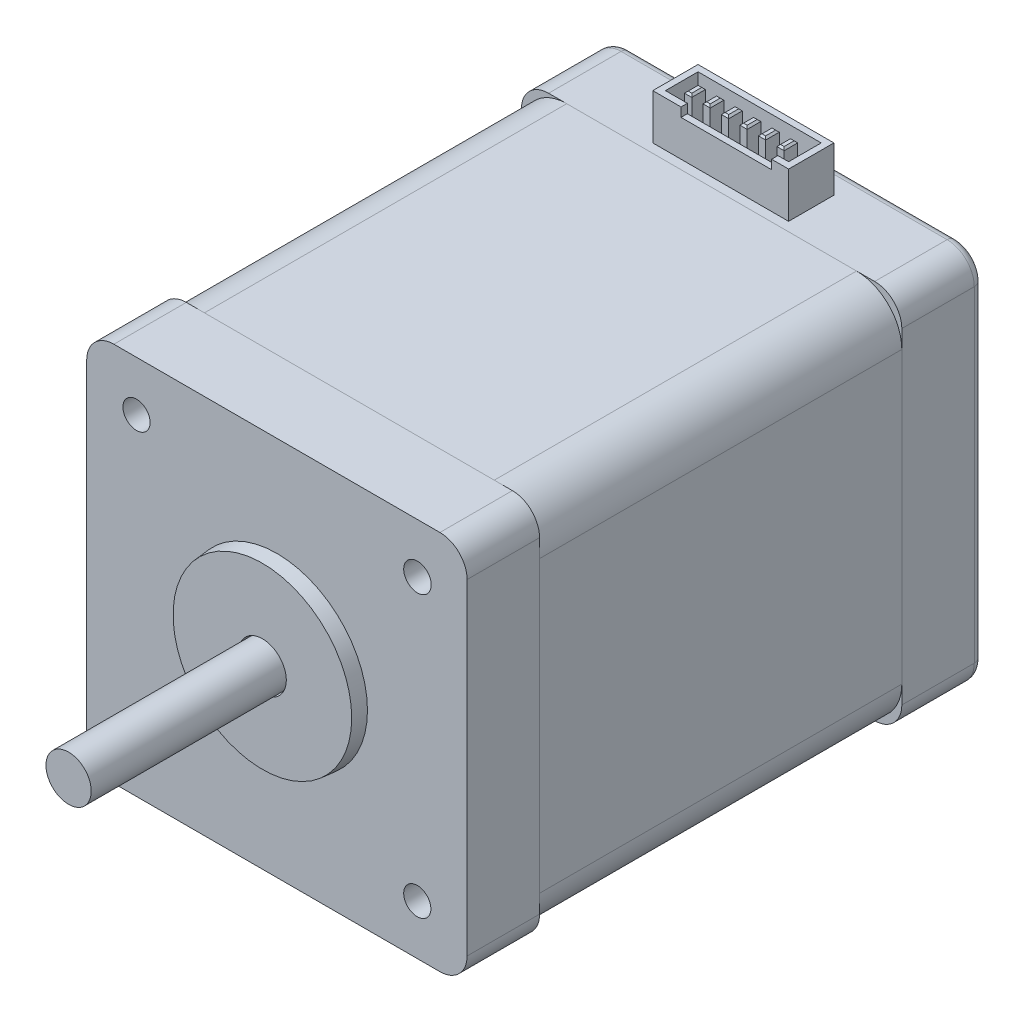
SolidWorks part; units mm, degrees
material "氧化铝"
ref_plane "前视基准面" through (0, 0, 0) normal (0, 0, 1) x (1, 0, 0)
ref_plane "上视基准面" through (0, 0, 0) normal (0, 1, 0) x (1, 0, 0)
ref_plane "右视基准面" through (0, 0, 0) normal (1, 0, 0) x (0, 0, -1)
sketch "草图1" plane through (0, 0, 0) normal (0, 0, 1) x (1, 0, 0)
  line L0 (0, 21) -> (0, -21) construction
  line L1 (-18, 21) -> (18, 21)
  line L2 (-21, 18) -> (-21, -18)
  line L3 (-18, -21) -> (18, -21)
  line L4 (21, 18) -> (21, -18)
  line L5 (-21, 21) -> (21, -21) construction
  line L6 (-21, -21) -> (21, 21) construction
  line L7 (-15.5, 15.5) -> (15.5, 15.5) construction
  line L8 (-15.5, 15.5) -> (-15.5, -15.5) construction
  line L9 (-15.5, -15.5) -> (15.5, -15.5) construction
  line L10 (15.5, 15.5) -> (15.5, -15.5) construction
  line L11 (-15.5, 15.5) -> (15.5, -15.5) construction
  line L12 (-15.5, -15.5) -> (15.5, 15.5) construction
  line L13 (-21, 0) -> (21, 0) construction
  circle A0 centre (-15.5, 15.5) radius 1.5
  circle A1 centre (15.5, 15.5) radius 1.5
  circle A2 centre (15.5, -15.5) radius 1.5
  circle A3 centre (-15.5, -15.5) radius 1.5
  arc A4 (-18, -21) -> (-21, -18) centre (-18, -18) cw
  arc A5 (18, -21) -> (21, -18) centre (18, -18) ccw
  arc A6 (21, 18) -> (18, 21) centre (18, 18) ccw
  arc A7 (-21, 18) -> (-18, 21) centre (-18, 18) cw
  point P0 (0, 0)
  point P6 (0, 0)
  dimension "D4" = 3
  dimension "D5" = 3
  dimension "D1" = 42
  dimension "D2" = 42
  dimension "D3" = 31
extrude "凸台-拉伸1" add sketch "草图1" along normal blind 8
sketch "草图4" plane through (0, 0, 8) normal (0, 0, 1) x (1, 0, 0)
  circle A0 centre (0, 0) radius 2.5
  dimension "D1" = 5
extrude "凸台-拉伸2" add sketch "草图4" along normal blind 23
sketch "草图9" plane through (0, 0, 0) normal (0, 0, -1) x (-1, 0, 0)
  line L1 (-21, 21) -> (21, 21)
  line L2 (-21, 21) -> (-21, -21)
  line L3 (-21, -21) -> (21, -21)
  line L4 (21, 21) -> (21, -21)
  line L5 (-21, 21) -> (21, -21) construction
  line L6 (-21, -21) -> (21, 21) construction
  point P0 (0, 0)
  dimension "D1" = 42
  dimension "D2" = 42
extrude "凸台-拉伸7" add sketch "草图9" along normal blind 40 separate body
sketch "草图10" plane through (0, 0, -40) normal (0, 0, -1) x (-1, 0, 0)
  line L1 (-21, 21) -> (21, 21)
  line L2 (-21, 21) -> (-21, -21)
  line L3 (-21, -21) -> (21, -21)
  line L4 (21, 21) -> (21, -21)
extrude "凸台-拉伸8" add sketch "草图10" along normal blind 9 separate body
fillet "圆角1" radius 3 4 edges at (21, -21, -44.5) (-21, -21, -44.5) (-21, 21, -44.5) (21, 21, -44.5)
fillet "圆角2" radius 5 4 edges at (-21, -21, -20) (-21, 21, -20) (21, 21, -20) (21, -21, -20)
sketch "草图12" plane through (0, 0, 8) normal (0, 0, 1) x (1, 0, 0)
  circle A0 centre (-15.5, 15.5) radius 1.5
  circle A1 centre (15.5185, 15.5) radius 1.5185
  circle A2 centre (-15.5, -15.5) radius 1.5
  circle A3 centre (15.5, -15.5) radius 1.5
extrude "切除-拉伸1" cut sketch "草图12" against normal through all
sketch "草图13" plane through (0, 0, -49) normal (0, 0, -1) x (-1, 0, 0)
  circle A0 centre (0, 0) radius 2.5
extrude "凸台-拉伸9" [suppressed] add sketch "草图13" along normal blind 12
sketch "草图14" plane through (0, 21, 0) normal (0, 1, 0) x (1, 0, 0)
  line L0 (-18, 49) -> (18, 49) construction
  line L1 (-7.5, 46) -> (7.5, 46)
  line L2 (-7.5, 46) -> (-7.5, 41)
  line L3 (-7.5, 41) -> (7.5, 41)
  line L4 (7.5, 46) -> (7.5, 41)
  line L5 (-6.8, 45.3) -> (6.8, 45.3)
  line L6 (6.8, 45.3) -> (6.8, 41.7)
  line L7 (-6.8, 41.7) -> (6.8, 41.7)
  line L8 (-6.8, 45.3) -> (-6.8, 41.7)
  line L9 (-3.66, 44.2073) -> (-2.86, 44.2073)
  line L10 (-5.7, 44.2073) -> (-4.9, 44.2073)
  line L11 (-5.7, 44.2073) -> (-5.7, 42.7073)
  line L12 (-5.7, 42.7073) -> (-4.9, 42.7073)
  line L13 (-4.9, 44.2073) -> (-4.9, 42.7073)
  line L14 (-5.7, 44.2073) -> (-4.9, 42.7073) construction
  line L15 (-5.7, 42.7073) -> (-4.9, 44.2073) construction
  line L16 (-3.66, 44.2073) -> (-3.66, 42.7073)
  line L17 (-3.66, 42.7073) -> (-2.86, 42.7073)
  line L18 (-2.86, 44.2073) -> (-2.86, 42.7073)
  line L19 (-3.66, 44.2073) -> (-2.86, 42.7073) construction
  line L20 (-3.66, 42.7073) -> (-2.86, 44.2073) construction
  line L21 (-1.62, 44.2073) -> (-0.82, 44.2073)
  line L22 (-1.62, 44.2073) -> (-1.62, 42.7073)
  line L23 (-1.62, 42.7073) -> (-0.82, 42.7073)
  line L24 (-0.82, 44.2073) -> (-0.82, 42.7073)
  line L25 (-1.62, 44.2073) -> (-0.82, 42.7073) construction
  line L26 (-1.62, 42.7073) -> (-0.82, 44.2073) construction
  line L27 (0.42, 44.2073) -> (1.22, 44.2073)
  line L28 (0.42, 44.2073) -> (0.42, 42.7073)
  line L29 (0.42, 42.7073) -> (1.22, 42.7073)
  line L30 (1.22, 44.2073) -> (1.22, 42.7073)
  line L31 (0.42, 44.2073) -> (1.22, 42.7073) construction
  line L32 (0.42, 42.7073) -> (1.22, 44.2073) construction
  line L33 (2.46, 44.2073) -> (3.26, 44.2073)
  line L34 (2.46, 44.2073) -> (2.46, 42.7073)
  line L35 (2.46, 42.7073) -> (3.26, 42.7073)
  line L36 (3.26, 44.2073) -> (3.26, 42.7073)
  line L37 (2.46, 44.2073) -> (3.26, 42.7073) construction
  line L38 (2.46, 42.7073) -> (3.26, 44.2073) construction
  line L39 (4.5, 44.2073) -> (5.3, 44.2073)
  line L40 (4.5, 44.2073) -> (4.5, 42.7073)
  line L41 (4.5, 42.7073) -> (5.3, 42.7073)
  line L42 (5.3, 44.2073) -> (5.3, 42.7073)
  line L43 (4.5, 44.2073) -> (5.3, 42.7073) construction
  line L44 (4.5, 42.7073) -> (5.3, 44.2073) construction
  line L45 (0, 49) -> (0, 46) construction
  point P11 (-5.3, 43.4573)
  point P18 (-3.26, 43.4573)
  point P23 (-1.22, 43.4573)
  point P28 (0.82, 43.4573)
  point P33 (2.86, 43.4573)
  point P38 (4.9, 43.4573)
  dimension "D1" = 15
  dimension "D2" = 5
  dimension "D3" = 3
  dimension "D4" = 0.7
  dimension "D5" = 1.5
  dimension "D6" = 0.8
  dimension "D8" = 1.5
  dimension "D9" = 1.5
  dimension "D7" = 6
extrude "凸台-拉伸10" add sketch "草图14" along normal blind 5 contours L4 L1 L2 L3 L8 L5 L6 L7 | L13 L10 L11 L12 | L24 L21 L22 L23 | L42 L39 L40 L41 | L36 L33 L34 L35 | L9 L18 L17 L16 | L27 L30 L29 L28
chamfer "倒角1" distance 0.2 angle 45 24 edges at (4.9, 26, -42.7073) (4.5, 26, -43.4573) (4.9, 26, -44.2073) (5.3, 26, -43.4573) (2.86, 26, -42.7073) (2.46, 26, -43.4573) (2.86, 26, -44.2073) (3.26, 26, -43.4573) (0.82, 26, -44.2073) (1.22, 26, -43.4573) (0.82, 26, -42.7073) (0.42, 26, -43.4573) (-1.22, 26, -42.7073) (-1.62, 26, -43.4573) (-1.22, 26, -44.2073) (-0.82, 26, -43.4573) (-3.26, 26, -44.2073) (-2.86, 26, -43.4573) (-3.26, 26, -42.7073) (-3.66, 26, -43.4573) (-5.3, 26, -42.7073) (-5.7, 26, -43.4573) (-5.3, 26, -44.2073) (-4.9, 26, -43.4573)
sketch "草图15" plane through (0, 0, -41) normal (0, 0, 1) x (1, 0, 0)
  line L0 (0.62, 26) -> (0.62, 22.2151) construction
  line L1 (-4.38, 26) -> (-4.38, 25)
  line L2 (-7.5, 26) -> (7.5, 26) construction
  line L3 (-4.38, 25) -> (5.62, 25)
  line L4 (5.62, 26) -> (5.62, 25)
  line L5 (-4.38, 26) -> (5.62, 26)
  point P9 (0.62, 25)
  dimension "D1" = 5
  dimension "D2" = 1
extrude "切除-拉伸2" cut sketch "草图15" against normal up to next (0.7 mm away)
fillet "圆角3" radius 1 8 edges at (20.1213, 20.1213, -49) (-20.1213, 20.1213, -49) (-21, 0, -49) (-20.1213, -20.1213, -49) (0, -21, -49) (20.1213, -20.1213, -49) (21, 0, -49) (0, 21, -49)
sketch "草图16" plane through (0, 0, 8) normal (0, 0, 1) x (1, 0, 0)
  circle A0 centre (0, 0) radius 10
  circle A1 centre (0, 0) radius 2.5 construction
  circle A2 centre (0, 0) radius 2.5
  dimension "D1" = 20
extrude "凸台-拉伸11" add sketch "草图16" along normal blind 1.6 draft 5
sketch "草图17" plane through (0, 0, -49) normal (0, 0, -1) x (-1, 0, 0)
  circle A0 centre (0, 0) radius 2.5
  dimension "D1" = 5
extrude "凸台-拉伸12" [suppressed] add sketch "草图17" along normal blind 15
